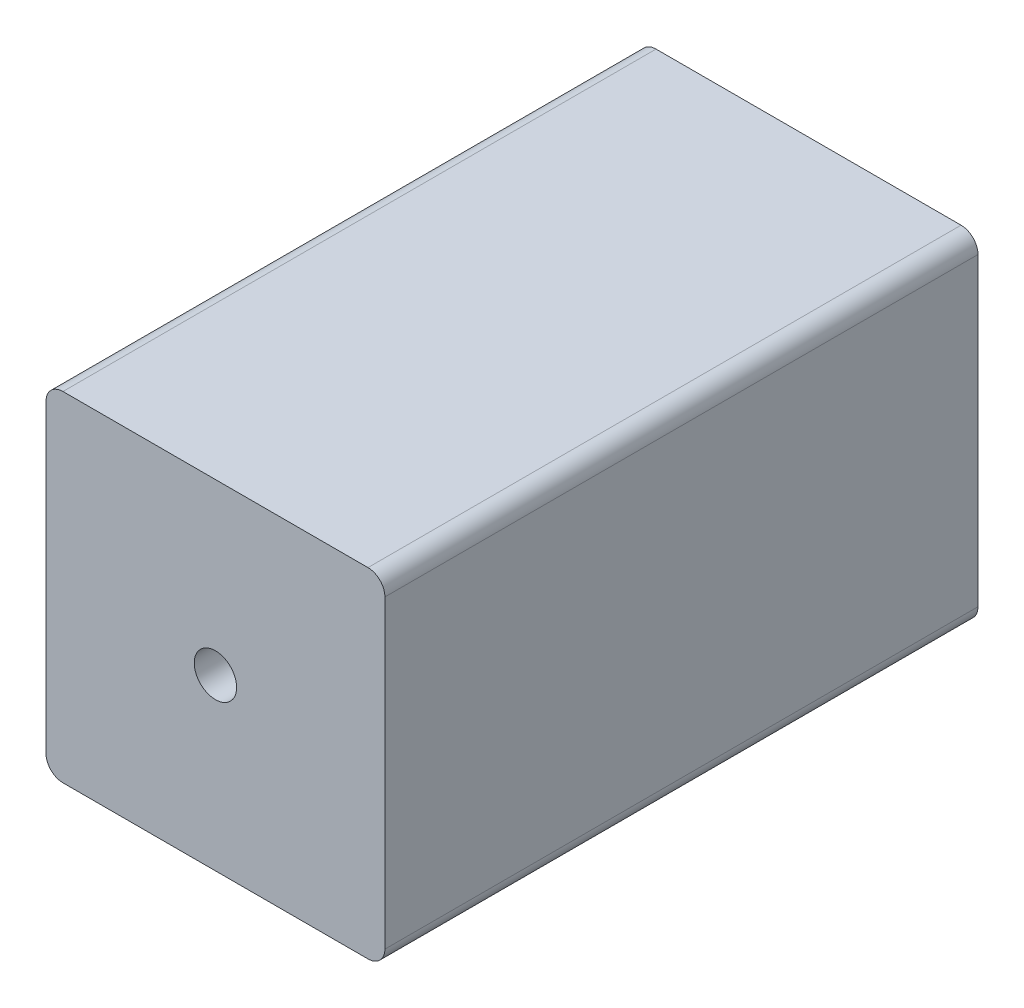
SolidWorks part; units mm, degrees
ref_plane "Front Plane" through (0, 0, 0) normal (0, 0, 1) x (1, 0, 0)
ref_plane "Top Plane" through (0, 0, 0) normal (0, 1, 0) x (1, 0, 0)
ref_plane "Right Plane" through (0, 0, 0) normal (1, 0, 0) x (0, 0, -1)
sketch "Sketch1" plane through (0, 0, 0) normal (0, 0, 1) x (1, 0, 0)
  line L1 (-20, -20) -> (20, -20)
  line L2 (-20, -20) -> (-20, 20)
  line L3 (-20, 20) -> (20, 20)
  line L4 (20, -20) -> (20, 20)
  line L5 (-20, -20) -> (20, 20) construction
  line L6 (-20, 20) -> (20, -20) construction
  circle A0 centre (0, 0) radius 2.5
  point P0 (0, 0)
  dimension "D3" = 5
  dimension "D1" = 40
  dimension "D2" = 40
extrude "Boss-Extrude1" add sketch "Sketch1" along normal mid plane 70
fillet "Fillet1" radius 2 4 edges at (20, -20, 0) (-20, -20, 0) (-20, 20, 0) (20, 20, 0)
sketch "Sketch2" plane through (0, 20, 0) normal (0, 1, 0) x (1, 0, 0)
  line L0 (0, 958.3172) -> (0, -945.7078) construction
  line L2 (18, 35) -> (-18, 35) construction
  line L3 (18, -35) -> (-18, -35) construction
  point P3 (0, -565)
  point P4 (0, 565)
  dimension "D1" = 600
  dimension "D2" = 600
hole_wizard "Ø4.5 (4.5) Diameter Hole1" [suppressed] positions "Sketch3" profile "Sketch4" hole size "Ø4.5" standard "ISO"
sketch "Sketch3" plane through (0, 20, 0) normal (0, 1, 0) x (1, 0, 0)
  point P0 (0, -300)
  point P3 (0, 300)
sketch "Sketch4" plane through (0, 20, 300) normal (1, 0, 0) x (0, 0, 1)
  line L0 (0, 0) -> (0, 40)
  line L1 (0, 40) -> (2.25, 40)
  line L2 (2.25, 40) -> (2.25, 0)
  line L5 (2.25, 0) -> (0, 0)
  line L11 (0, -6.35) -> (0, 107.95) construction
  dimension "Thru Hole Dia." = 4.5
  dimension "Thru Hole Depth" = 40
sketch "Sketch5" plane through (0, -20, 0) normal (0, -1, 0) x (1, 0, 0)
  line L0 (0, 35) -> (0, -1000.0028) construction
  line L1 (-18, 35) -> (18, 35) construction
  point P5 (0, 500)
  point P6 (0, 0)
  point P7 (0, -500)
  dimension "D1" = 500
  dimension "D2" = 500
hole_wizard "CBORE for M8 Hex Head Bolt1" [suppressed] positions "Sketch6" profile "Sketch7" counterbore size "M8" standard "ANSI Metric"
sketch "Sketch6" plane through (0, -20, 0) normal (0, -1, 0) x (-1, 0, 0)
  point P0 (0, 500)
  point P3 (0, 0)
  point P6 (0, -500)
sketch "Sketch7" plane through (0, -20, -500) normal (1, 0, 0) x (0, 0, -1)
  line L0 (0, 0) -> (0, 40)
  line L1 (0, 40) -> (4.5, 40)
  line L3 (4.5, 40) -> (4.5, 12.3)
  line L4 (4.5, 12.3) -> (9.005, 12.3)
  line L5 (9.005, 12.3) -> (9.005, 0)
  line L7 (9.005, 0) -> (0, 0)
  line L11 (0, -6.35) -> (0, 107.95) construction
  dimension "Thru Hole Dia." = 9
  dimension "Thru Hole Depth" = 40
  dimension "C'Bore Dia." = 18.01
  dimension "C'Bore Depth" = 12.3
hole_wizard "M8x1.25 Tapped Hole1" [suppressed] positions "Sketch8" profile "Sketch9" tap size "M8x1.25" standard "ANSI Metric"
sketch "Sketch8" plane through (0, 0, 335) normal (0, 0, 1) x (1, 0, 0)
  point P0 (0, 0)
sketch "Sketch9" plane through (0, 0, 335) normal (1, 0, 0) x (0, -1, 0)
  line L0 (0, 0) -> (0, 29.7929)
  line L1 (0, 29.7929) -> (3.4, 27.75)
  line L2 (3.4, 27.75) -> (3.4, 0)
  line L5 (3.4, 0) -> (0, 0)
  line L10 (0, 29.7929) -> (-3.4, 27.75) construction
  line L11 (0, -6.35) -> (0, 107.95) construction
  dimension "Tap Drill Dia." = 6.8
  dimension "Tap Drill Depth" = 27.75
  dimension "Drill Angle" = 118
cosmetic thread "Hole Thread1" [suppressed] parameters "D1"=24, "D2"=8
mirror "Mirror1" [suppressed] about plane through (0, 0, 0) normal (0, 0, 1)
cosmetic thread "Hole Thread2" [suppressed] parameters "D1"=24, "D2"=8
